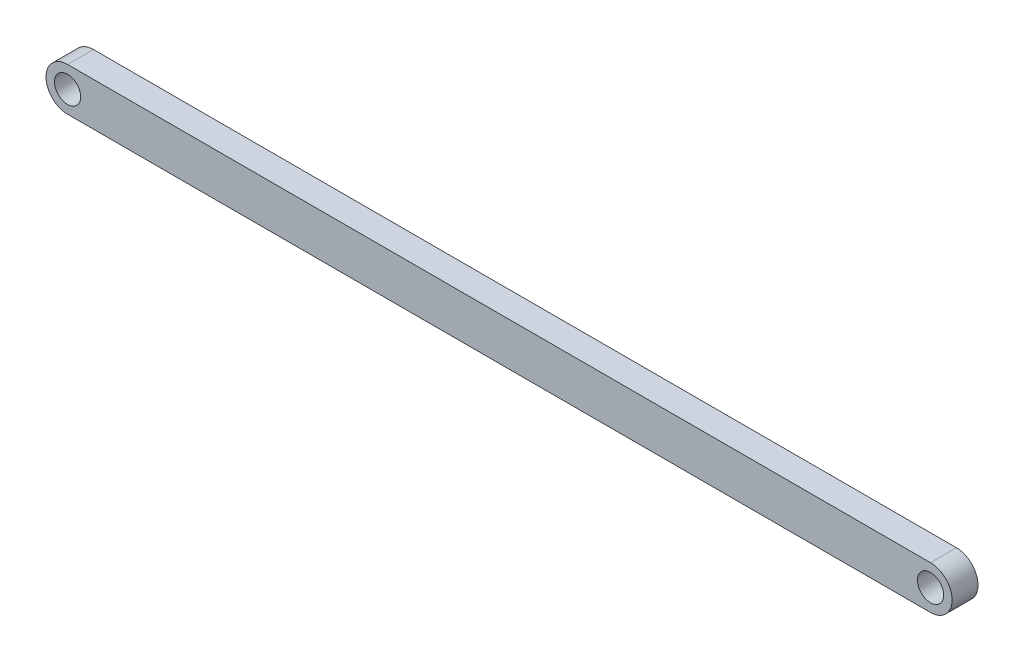
SolidWorks part; units mm, degrees
ref_plane "Plan de face" through (0, 0, 0) normal (0, 0, 1) x (1, 0, 0)
ref_plane "Plan de dessus" through (0, 0, 0) normal (0, 1, 0) x (1, 0, 0)
ref_plane "Plan de droite" through (0, 0, 0) normal (1, 0, 0) x (0, 0, -1)
sketch "Esquisse1" plane through (0, 0, 0) normal (0, 0, 1) x (1, 0, 0)
  line L0 (-76.2061, 0) -> (423.7939, 0) construction
  line L1 (-76.2061, 12.5) -> (423.7939, 12.5)
  line L2 (-76.2061, -12.5) -> (423.7939, -12.5)
  arc A0 (-76.2061, 12.5) -> (-76.2061, -12.5) centre (-76.2061, 0) ccw
  arc A1 (423.7939, -12.5) -> (423.7939, 12.5) centre (423.7939, 0) ccw
  circle A2 centre (-76.2061, 0) radius 7.6
  circle A3 centre (423.7939, 0) radius 7.6
  point P3 (173.7939, 0)
  dimension "D1" = 15.2
  dimension "D2" = 15.2
extrude "Boss.-Extru.1" add sketch "Esquisse1" along normal blind 15
